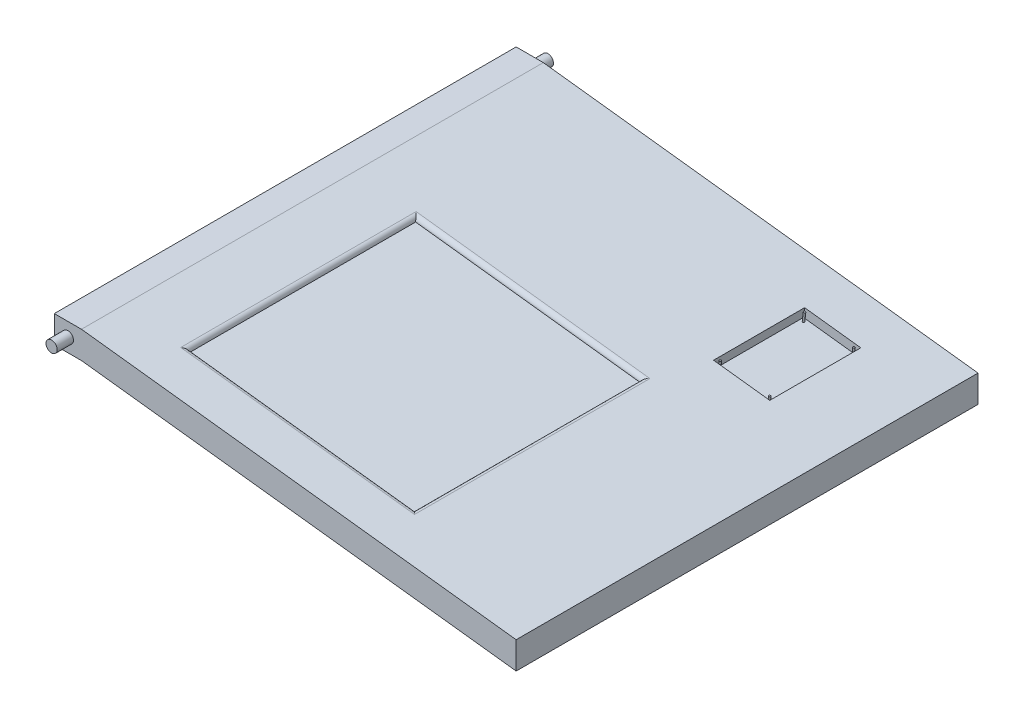
SolidWorks part; units mm, degrees
ref_plane "Front Plane" through (0, 0, 0) normal (0, 0, 1) x (1, 0, 0)
ref_plane "Top Plane" through (0, 0, 0) normal (0, 1, 0) x (1, 0, 0)
ref_plane "Right Plane" through (0, 0, 0) normal (1, 0, 0) x (0, 0, -1)
sketch "Sketch1" plane through (0, 0, 0) normal (0, 0, 1) x (1, 0, 0)
  line L0 (-65.6672, 100.1607) -> (-65.6672, 70.1607)
  line L1 (-65.6672, 70.1607) -> (-35.6672, 70.1607)
  line L2 (-35.6672, 70.1607) -> (444.3328, 13.261)
  line L3 (444.3328, 13.261) -> (444.3328, 43.261)
  line L4 (444.3328, 43.261) -> (-35.6672, 100.1607)
  line L5 (-35.6672, 100.1607) -> (-65.6672, 100.1607)
  circle A0 centre (-50.6672, 85.1607) radius 6.1819
  dimension "D1" = 480
  dimension "D2" = 30
  dimension "D3" = 30
  dimension "D4" = 30
  dimension "D5" = 15
  dimension "D6" = 15
  dimension "D7" = 30
extrude "Boss-Extrude2" add sketch "Sketch1" along normal blind 510
sketch "Sketch2" plane through (0, 0, 510) normal (0, 0, 1) x (1, 0, 0)
  circle A0 centre (-50.6672, 85.1607) radius 6.1819
extrude "Boss-Extrude3" add sketch "Sketch2" against normal blind 471 and the other way blind 18
sketch "Sketch3" plane through (0, 0, 0) normal (0, 0, -1) x (-1, 0, 0)
  circle A0 centre (50.6672, 85.1607) radius 6.1819
extrude "Boss-Extrude4" add sketch "Sketch3" along normal blind 20 separate body
sketch "Sketch4" plane through (11.2144, 94.6033, 0) normal (0.1177, 0.993, 0) x (0.993, -0.1177, 0)
  line L0 (436.1509, -510) -> (436.1509, 0) construction
  line L1 (293.6509, -150.5) -> (356.1509, -150.5)
  line L2 (293.6509, -150.5) -> (293.6509, -50)
  line L3 (293.6509, -50) -> (356.1509, -50)
  line L4 (356.1509, -150.5) -> (356.1509, -50)
  line L5 (436.1509, 0) -> (-47.2098, 0) construction
  line L6 (324.9009, -50) -> (324.9009, -163.8885) construction
  line L7 (324.9009, -163.8885) -> (356.1509, -100.25) construction
  line L8 (356.1509, -100.25) -> (283.5378, -100.25) construction
  line L9 (293.6509, -100.25) -> (366.2639, -100.25) construction
  circle A0 centre (297.4009, -53.75) radius 1
  circle A1 centre (352.4009, -53.75) radius 1
  circle A2 centre (352.4009, -146.75) radius 1
  circle A3 centre (297.4009, -146.75) radius 1
  dimension "D7" = 2
  dimension "D1" = 100.5
  dimension "D2" = 62.5
  dimension "D3" = 80
  dimension "D4" = 50
  dimension "D5" = 3.75
  dimension "D6" = 3.75
extrude "Cut-Extrude1" cut sketch "Sketch4" against normal blind 10
sketch "Sketch5" plane through (11.2144, 94.6033, 0) normal (0.1177, 0.993, 0) x (0.993, -0.1177, 0)
  line L0 (436.1509, -510) -> (-47.2098, -510) construction
  line L1 (22.7902, -210) -> (272.7902, -210)
  line L2 (22.7902, -210) -> (22.7902, -460)
  line L3 (22.7902, -460) -> (272.7902, -460)
  line L4 (272.7902, -210) -> (272.7902, -460)
  line L5 (-47.2098, -510) -> (-47.2098, 0) construction
  dimension "D1" = 50
  dimension "D2" = 70
  dimension "D3" = 250
  dimension "D4" = 250
extrude "Cut-Extrude2" cut sketch "Sketch5" against normal blind 10
fillet "Fillet1" radius 5 4 edges at (282.1079, 62.4913, 335) (157.977, 77.2059, 460) (33.8461, 91.9205, 335) (157.977, 77.2059, 210)
sketch "Sketch6" plane through (10.0372, 84.6729, 0) normal (0.1177, 0.993, 0) x (0.993, -0.1177, 0)
  line L0 (272.7902, -460) -> (272.7902, -210) construction
  line L1 (22.7902, -460) -> (272.7902, -460)
  line L2 (22.7902, -460) -> (22.7902, -210)
  line L3 (22.7902, -210) -> (272.7902, -210)
  line L4 (272.7902, -460) -> (272.7902, -210)
  line L5 (272.7902, -210) -> (22.7902, -210) construction
extrude "Cut-Extrude3" cut sketch "Sketch6" against normal blind 885
sketch "Sketch7" plane through (7.7074, 65.019, 0) normal (-0.1177, -0.993, 0) x (0.993, -0.1177, 0)
  line L1 (22.7902, 460) -> (272.7902, 460)
  line L2 (22.7902, 460) -> (22.7902, 210)
  line L3 (22.7902, 210) -> (272.7902, 210)
  line L4 (272.7902, 460) -> (272.7902, 210)
extrude "Boss-Extrude5" add sketch "Sketch7" against normal blind 25
